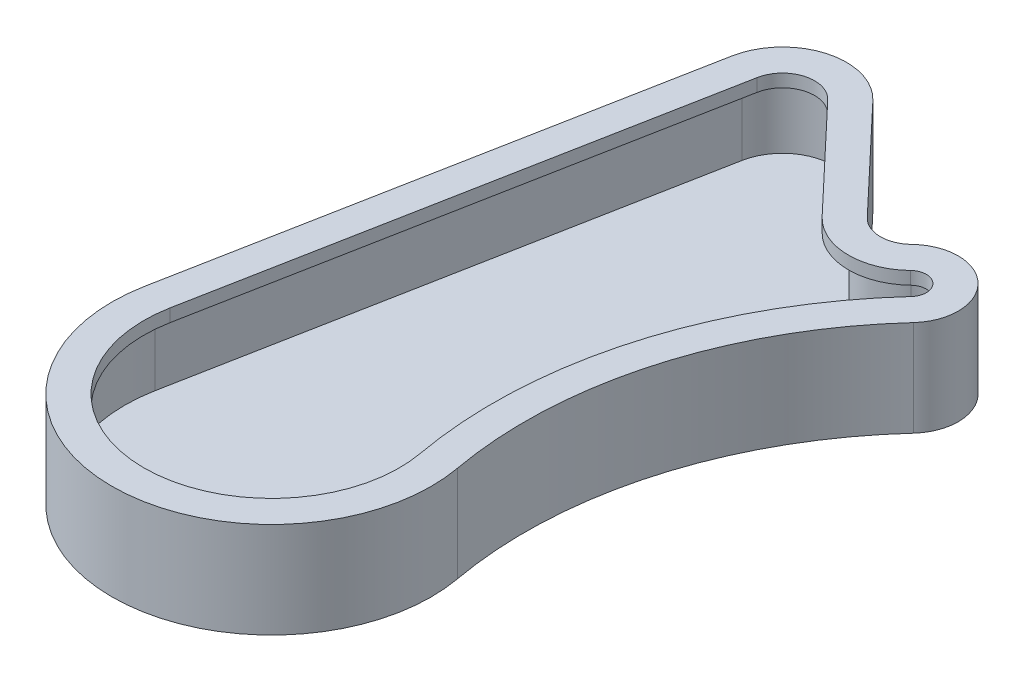
SolidWorks part; units mm, degrees
ref_plane "Front Plane" through (0, 0, 0) normal (0, 0, 1) x (1, 0, 0)
ref_plane "Top Plane" through (0, 0, 0) normal (0, 1, 0) x (1, 0, 0)
ref_plane "Right Plane" through (0, 0, 0) normal (1, 0, 0) x (0, 0, -1)
sketch "Sketch1" plane through (0, 0, 0) normal (0, 1, 0) x (1, 0, 0)
  line L0 (0, 0) -> (0, 80) construction
  line L1 (-24.5566, 4.6875) -> (-9.8226, 81.875)
  line L2 (7.2643, 86.8724) -> (22.6932, 70.5638)
  arc A0 (-24.5566, 4.6875) -> (24.5957, 4.4778) centre (0, 0) ccw
  arc A1 (7.2643, 86.8724) -> (-9.8226, 81.875) centre (0, 80) ccw
  arc A2 (40.5391, 59.9435) -> (29.7952, 70.4) centre (35, 65) ccw
  arc A3 (24.5957, 4.4778) -> (40.5391, 59.9435) centre (88.5446, 16.1202) cw
  arc A4 (22.6932, 70.5638) -> (29.7952, 70.4) centre (26.3253, 74) ccw
  dimension "D1" = 50
  dimension "D2" = 20
  dimension "D3" = 115
  dimension "D4" = 15
  dimension "D5" = 97.5
  dimension "D6" = 67.5
  dimension "D7" = 65
  dimension "D8" = 5
  dimension "D9" = 21
extrude "Boss-Extrude1" add sketch "Sketch1" along normal blind 15
sketch "Sketch2" plane through (0, 15, 0) normal (0, 1, 0) x (1, 0, 0)
  line L6 (21.2403, 69.1893) -> (5.8114, 85.4979)
  line L7 (-7.8581, 81.5) -> (-22.5921, 4.3125)
  line L8 (21.2403, 69.1893) -> (5.8114, 85.4979)
  line L9 (-7.8581, 81.5) -> (-22.5921, 4.3125)
  arc A15 (-22.5921, 4.3125) -> (22.6281, 4.1196) centre (0, 0) ccw
  arc A16 (39.062, 61.2919) -> (22.6281, 4.1196) centre (88.5446, 16.1202) ccw
  arc A17 (39.062, 61.2919) -> (31.1831, 68.96) centre (35, 65) ccw
  arc A18 (21.2403, 69.1893) -> (31.1831, 68.96) centre (26.3253, 74) ccw
  arc A19 (5.8114, 85.4979) -> (-7.8581, 81.5) centre (0, 80) ccw
  arc A20 (-22.5921, 4.3125) -> (22.6281, 4.1196) centre (0, 0) ccw
  arc A21 (39.062, 61.2919) -> (22.6281, 4.1196) centre (88.5446, 16.1202) ccw
  arc A22 (39.062, 61.2919) -> (31.1831, 68.96) centre (35, 65) ccw
  arc A23 (21.2403, 69.1893) -> (31.1831, 68.96) centre (26.3253, 74) ccw
  arc A24 (5.8114, 85.4979) -> (-7.8581, 81.5) centre (0, 80) ccw
  dimension "D1" = 2
extrude "Cut-Extrude1" cut sketch "Sketch2" against normal blind 13
sketch "Sketch7" plane through (0, 15, 0) normal (0, 1, 0) x (1, 0, 0)
  line L0 (-4.9113, 80.9375) -> (-19.6453, 3.75)
  line L1 (19.061, 67.1276) -> (3.6321, 83.4362)
  line L2 (22.6932, 70.5638) -> (7.2643, 86.8724)
  line L3 (-9.8226, 81.875) -> (-24.5566, 4.6875)
  line L4 (22.6932, 70.5638) -> (7.2643, 86.8724)
  line L5 (-9.8226, 81.875) -> (-24.5566, 4.6875)
  arc A0 (-19.6453, 3.75) -> (19.6766, 3.5823) centre (0, 0) ccw
  arc A1 (36.8464, 63.3145) -> (19.6766, 3.5823) centre (88.5446, 16.1202) ccw
  arc A2 (36.8464, 63.3145) -> (33.2651, 66.8) centre (35, 65) ccw
  arc A3 (19.061, 67.1276) -> (33.2651, 66.8) centre (26.3253, 74) ccw
  arc A4 (3.6321, 83.4362) -> (-4.9113, 80.9375) centre (0, 80) ccw
  arc A5 (-24.5566, 4.6875) -> (24.5957, 4.4778) centre (0, 0) ccw
  arc A6 (40.5391, 59.9435) -> (24.5957, 4.4778) centre (88.5446, 16.1202) ccw
  arc A7 (40.5391, 59.9435) -> (29.7952, 70.4) centre (35, 65) ccw
  arc A8 (22.6932, 70.5638) -> (29.7952, 70.4) centre (26.3253, 74) ccw
  arc A9 (7.2643, 86.8724) -> (-9.8226, 81.875) centre (0, 80) ccw
  arc A10 (-24.5566, 4.6875) -> (24.5957, 4.4778) centre (0, 0) ccw
  arc A11 (40.5391, 59.9435) -> (24.5957, 4.4778) centre (88.5446, 16.1202) ccw
  arc A12 (40.5391, 59.9435) -> (29.7952, 70.4) centre (35, 65) ccw
  arc A13 (22.6932, 70.5638) -> (29.7952, 70.4) centre (26.3253, 74) ccw
  arc A14 (7.2643, 86.8724) -> (-9.8226, 81.875) centre (0, 80) ccw
  dimension "D1" = 0
  dimension "D2" = 5
extrude "Boss-Extrude2" add sketch "Sketch7" against normal blind 2
